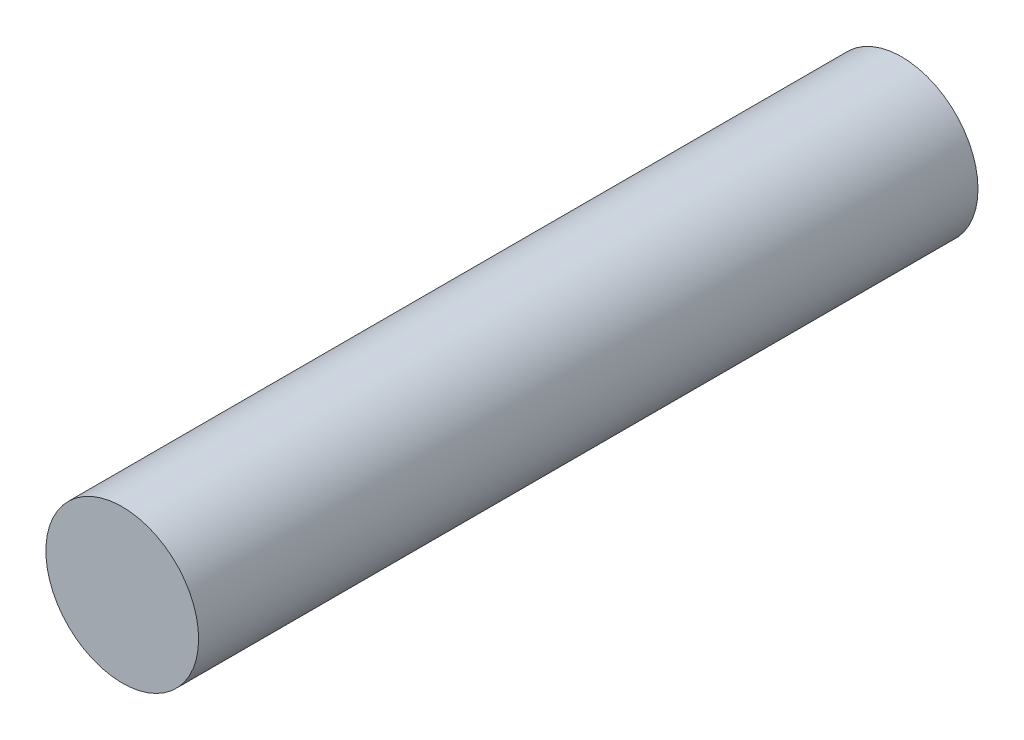
SolidWorks part; units mm, degrees
ref_plane "Front Plane" through (0, 0, 0) normal (0, 0, 1) x (1, 0, 0)
ref_plane "Top Plane" through (0, 0, 0) normal (0, 1, 0) x (1, 0, 0)
ref_plane "Right Plane" through (0, 0, 0) normal (1, 0, 0) x (0, 0, -1)
sketch "Sketch1" plane through (0, 0, 0) normal (0, 0, 1) x (1, 0, 0)
  circle A0 centre (0, 0) radius 99.965
  dimension "D1" = 199.93
extrude "Boss-Extrude1" add sketch "Sketch1" along normal blind 1020
